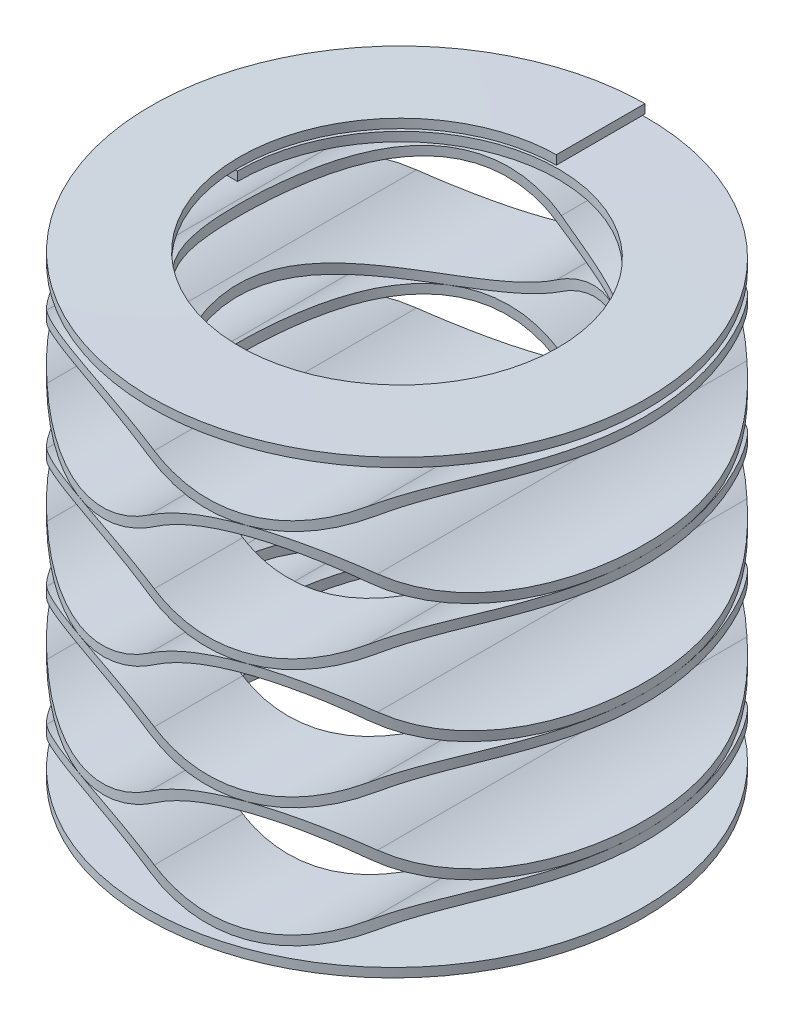
SolidWorks part; units mm, degrees
ref_plane "Front Plane" through (0, 0, 0) normal (0, 0, 1) x (1, 0, 0)
ref_plane "Top Plane" through (0, 0, 0) normal (0, 1, 0) x (1, 0, 0)
ref_plane "Right Plane" through (0, 0, 0) normal (1, 0, 0) x (0, 0, -1)
sketch "Sketch1" plane through (0, 0, 0) normal (0, 1, 0) x (1, 0, 0)
  line L0 (-5.5499, 0) -> (57.9501, 0) construction
  line L1 (3.5687, 0) -> (5.5499, 0) construction
  circle A0 centre (0, 0) radius 3.5687
  circle A1 centre (0, 0) radius 5.5499
  point P6 (-3.5687, 0)
  point P7 (3.5687, 0)
  point P8 (5.5499, 0)
  point P11 (4.5593, 0)
  dimension "Number of Waves" = 63.5
sketch "Sketch2" plane through (0, 0, 0) normal (0, 0, 1) x (1, 0, 0)
  line L0 (0, 4.8895) -> (0, -4.8895) construction
  line L1 (5.5499, 0) -> (-5.5499, 0) construction
  line L2 (-5.5499, -4.8895) -> (-5.5499, -4.6863) construction
  point P3 (-5.5499, 4.8895)
  point P4 (0, 4.8895)
  point P5 (2.1215, -4.4053)
  point P6 (-2.1215, -4.4053)
  point P7 (-4.7669, -1.088)
  point P8 (3.8228, 3.0486)
  point P9 (4.7669, -1.088)
  point P10 (-3.8228, 3.0486)
  point P11 (0, 0)
  point P18 (-5.5499, -4.7879)
  dimension "Height" = 9.779
  dimension "Thickness" = 0.2032
  dimension "Number of Turns" = 7
sketch "Sketch3" plane through (0, 0, 0) normal (0, 0, 1) x (1, 0, 0)
  line L0 (0, -4.8895) -> (0, -3.3474) construction
  line L1 (0, 4.8895) -> (0, -4.8895) construction
  line L2 (-5.5499, -4.8895) -> (-1.85, -4.8895) construction
  line L3 (0, -3.3474) -> (-5.5499, -3.3474) construction
  line L4 (-5.5499, -3.5506) -> (0, -3.5506) construction
  line L5 (-1.85, -4.8895) -> (-1.85, -3.5506) construction
  line L6 (-5.5499, -4.6863) -> (-1.85, -4.6863) construction
  arc A0 (-5.5499, -4.6863) -> (-3.6999, -4.1184) centre (-5.5499, -1.389) ccw
  arc A1 (-3.6999, -4.1184) -> (-1.85, -3.5506) centre (-1.85, -6.8478) cw
  dimension "D2" = 3.6999
  dimension "D3" = 0.2032
  dimension "D1" = 1.3389
surface "Surface-Extrude1" sketch "Sketch3" parameters "D1"=11.0998
ref_plane "Plane1" through (-1.85, 0, 0) normal (1, 0, 0) x (0, 0, -1)
mirror "Mirror1" about plane through (-1.85, 0, 0) normal (1, 0, 0)
ref_plane "Plane2" through (1.85, 0, 0) normal (1, 0, 0) x (0, 0, -1)
mirror "Mirror2" about plane through (1.85, 0, 0) normal (1, 0, 0)
surface "Surface-Knit1"
thicken "Thicken1" surfaces to thicken 107 thickness 0.2032 parameters "D1"=0.2032
ref_plane "Plane3" through (0, -3.3474, 0) normal (0, 1, 0) x (-1, 0, 0)
mirror "Mirror3" about plane through (0, -3.3474, 0) normal (0, 1, 0) of bodies 108
pattern_linear "LPattern1" count 5 spacing 2.6779 along (0, 1, 0) of bodies 108 109
sketch "Sketch4" plane through (0, 0, 0) normal (0, 1, 0) x (1, 0, 0)
  circle A0 centre (0, 0) radius 5.5499 construction
  circle A1 centre (0, 0) radius 5.5499
extrude "Cut-Extrude1" cut sketch "Sketch4" against normal through all both and the other way through all flip side to cut
sketch "Sketch5" plane through (0, 0, 0) normal (0, 1, 0) x (1, 0, 0)
  circle A0 centre (0, 0) radius 3.5687 construction
  circle A1 centre (0, 0) radius 3.5687
extrude "Cut-Extrude2" cut sketch "Sketch5" against normal through all both and the other way through all
sketch "Sketch6" plane through (0, 0, 0) normal (0, 0, 1) x (1, 0, 0)
  line L0 (0, 4.8895) -> (0, -4.8895) construction
  line L5 (5.5499, 4.6863) -> (-5.5499, 4.6863)
  line L6 (5.5499, 4.6863) -> (5.5499, -4.6863)
  line L7 (5.5499, -4.6863) -> (-5.5499, -4.6863)
  line L8 (-5.5499, 4.6863) -> (-5.5499, -4.6863)
  line L9 (0, -4.6863) -> (0, 4.6863) construction
  line L10 (5.5499, 0) -> (-5.5499, 0) construction
  point P0 (0, 0)
extrude "Cut-Extrude3" cut sketch "Sketch6" against normal through all both and the other way through all flip side to cut
ref_plane "Plane4" through (0, -4.7879, 0) normal (0, 1, 0) x (1, 0, 0)
sketch "Sketch7" plane through (0, -4.7879, 0) normal (0, 1, 0) x (1, 0, 0)
  circle A0 centre (0, 0) radius 4.5593
curve "Helix/Spiral1" pitch 0.254 height 0.3175 turns 1.25
sketch "Sketch8" plane through (0, 0, 0) normal (0, 0, 1) x (1, 0, 0)
  line L4 (-5.5499, -4.8895) -> (-5.5499, -4.6863)
  line L5 (-5.5499, -4.6863) -> (-3.5687, -4.6863)
  line L6 (-3.5687, -4.6863) -> (-3.5687, -4.8895)
  line L7 (-3.5687, -4.8895) -> (-5.5499, -4.8895)
  line L10 (0, 4.8895) -> (0, -4.8895) construction
  point P9 (-3.5687, 0)
sweep "Sweep1" add profiles "Sketch8" path "Helix/Spiral1"
mirror "Mirror4" about plane through (0, 0, 0) normal (0, 1, 0) of bodies 171
ref_plane "Plane5" through (0, 4.8895, 0) normal (0, 1, 0) x (1, 0, 0)
sketch "Sketch10" plane through (0, 4.8895, 0) normal (0, 1, 0) x (1, 0, 0)
  circle A0 centre (0, 0) radius 5.5499
ref_plane "Plane6" through (0, -4.8895, 0) normal (0, 1, 0) x (1, 0, 0)
sketch "Sketch11" plane through (0, -4.8895, 0) normal (0, 1, 0) x (1, 0, 0)
  circle A0 centre (0, 0) radius 6.96
equation "\"D2@Sketch3\" = \"For Hole Diameter@Sketch1\" /  ( \"Number of Waves@Sketch1\" + 0.5 ) "
equation "\"D3@Sketch3\" = \"Thickness@Sketch2\""
equation "\"D1@Thicken1\" = \"Thickness@Sketch2\""
equation "\"D1@LPattern1\" = \"Number of Turns@Sketch2\" / 2 + 1"
equation "\"D3@LPattern1\" =  (  ( \"Height@Sketch2\" - \"Thickness@Sketch2\" * 2 )  / \"Number of Turns@Sketch2\" )  * 2"
equation "\"D1@Sketch3\" =  ( \"Height@Sketch2\" - \"Thickness@Sketch2\" * 2 )  / \"Number of Turns@Sketch2\""
equation "\"D1@Surface-Extrude1\" = \"For Hole Diameter@Sketch1\""
equation "\"D4@Helix/Spiral1\"=\"Thickness@Sketch2\" + (\"Thickness@Sketch2\")*.25"
equation "\"D3@Helix/Spiral1\" = \"Thickness@Sketch2\" + .1"
